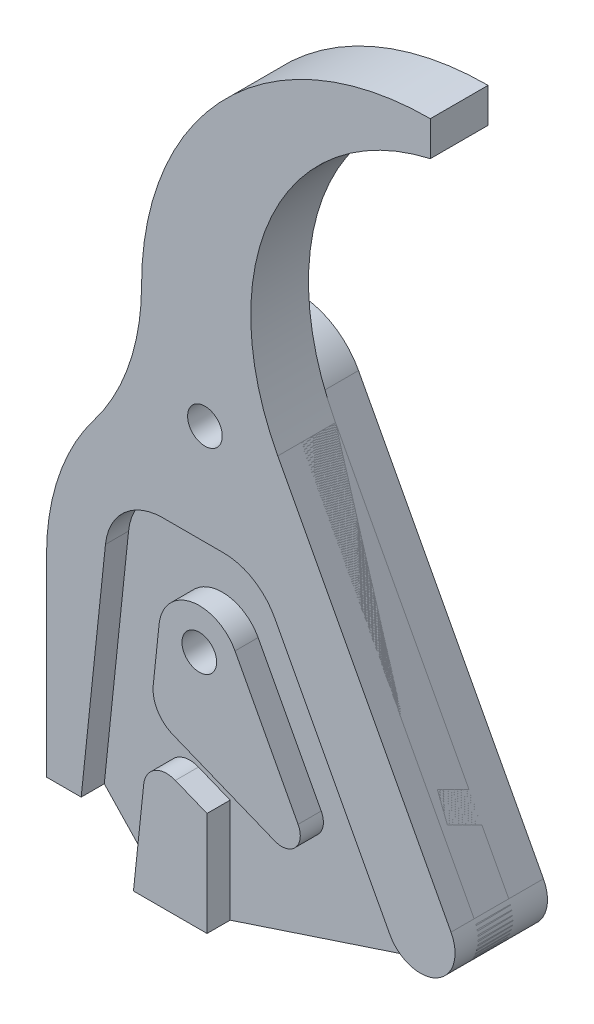
SolidWorks part; units mm, degrees
ref_plane "Alzado" through (0, 0, 0) normal (0, 0, 1) x (1, 0, 0)
ref_plane "Planta" through (0, 0, 0) normal (0, 1, 0) x (1, 0, 0)
ref_plane "Vista lateral" through (0, 0, 0) normal (1, 0, 0) x (0, 0, -1)
sketch "Croquis1" plane through (0, 0, 0) normal (0, 0, 1) x (1, 0, 0)
  line L0 (0, 0) -> (3.2081, 30.5226)
  line L1 (8.1807, 35) -> (13.4351, 35)
  line L2 (17.8498, 32.3474) -> (74.7762, -74.7155)
  line L3 (-45.5316, -5.3258) -> (-45.5316, 25.382)
  line L4 (0, 0) -> (0, 124.083) construction
  line L5 (14.4224, 28.1432) -> (19.8837, 17.8719)
  line L6 (7.8513, 26.8658) -> (7.3413, 22.014)
  line L7 (17.8498, 32.3474) -> (5.7848, 55.0384) construction
  line L8 (5.7848, 55.0384) -> (3.2081, 30.5226) construction
  line L9 (17.8538, 15.6175) -> (9.0466, 19.1759)
  line L10 (25.2121, 15.5) -> (11.8352, 15.5) construction
  line L11 (12.9137, 30) -> (5.536, 30) construction
  line L12 (6.4174, 22.7498) -> (9.4633, 17.0212) construction
  line L13 (5.0275, 0) -> (6.521, 14.2091)
  line L14 (9.2592, 15.8544) -> (17.7727, 12.4147)
  line L15 (6.3558, 16) -> (10.5824, 16) construction
  arc A0 (14.4224, 28.1432) -> (7.8513, 26.8658) centre (11.3321, 26.5) ccw
  arc A1 (17.8498, 32.3474) -> (13.4351, 35) centre (13.4351, 30) ccw
  arc A2 (8.1807, 35) -> (3.2081, 30.5226) centre (8.1807, 30) ccw
  arc A3 (7.3413, 22.014) -> (9.0466, 19.1759) centre (10.0771, 21.7264) ccw
  arc A4 (19.8837, 17.8719) -> (17.8538, 15.6175) centre (18.4585, 17.1142) cw
  arc A5 (6.521, 14.2091) -> (9.2592, 15.8544) centre (8.51, 14) cw
  dimension "D2" = 3.5
  dimension "D3" = 5
  dimension "D6" = 5
  dimension "D9" = 35
  dimension "D8" = 5
  dimension "D16" = 2
  dimension "D1" = 34
  dimension "D4" = 6
  dimension "D5" = 5
  dimension "D7" = 8.5
  dimension "D10" = 106
  dimension "D11" = 14.5
  dimension "D12" = 9.6
  dimension "D13" = 3
  dimension "D14" = 16
  dimension "D15" = 5
sketch "Croquis4" plane through (0, 0, 0) normal (0, 0, 1) x (1, 0, 0)
  line L0 (8.1807, 35) -> (13.4351, 35) construction
  line L1 (31.3321, 76.5) -> (69.3272, 76.5) construction
  line L2 (31.3321, 76.5) -> (31.3321, 73.5)
  line L3 (17.8538, 15.6175) -> (9.0466, 19.1759) construction
  line L5 (8.1807, 35) -> (13.4351, 35)
  line L6 (7.8513, 26.8658) -> (7.3413, 22.014)
  line L7 (7.8513, 26.8658) -> (7.3413, 22.014) construction
  line L8 (3.2081, 30.5226) -> (1.106, 10.5226)
  line L9 (0, 0) -> (3.2081, 30.5226) construction
  line L10 (17.8498, 32.3474) -> (27.8225, 13.5916)
  line L11 (17.8498, 32.3474) -> (74.7762, -74.7155) construction
  line L12 (6.521, 14.2091) -> (5.6316, 5.747)
  line L13 (14.4224, 28.1432) -> (19.8837, 17.8719) construction
  line L14 (17.8538, 15.6175) -> (9.0466, 19.1759)
  line L15 (1.106, 10.5226) -> (-1.894, 10.5226)
  line L16 (-1.894, 10.5226) -> (-1.894, 27.2014)
  line L17 (14.4224, 28.1432) -> (19.8837, 17.8719)
  line L18 (33.1201, 16.4084) -> (18.124, 44.6121)
  line L19 (5.0275, 0) -> (6.521, 14.2091) construction
  line L20 (9.2592, 15.8544) -> (12, 14.747)
  line L21 (9.2592, 15.8544) -> (17.7727, 12.4147) construction
  line L22 (12, 14.747) -> (12, 5.747)
  line L23 (12, 5.747) -> (5.6316, 5.747)
  line L25 (0, 0) -> (0, 124.083) construction
  line L26 (6.3321, 51.5) -> (-1.894, 27.2014) construction
  line L27 (17.8498, 32.3474) -> (5.7848, 55.0384) construction
  arc A0 (17.8498, 32.3474) -> (13.4351, 35) centre (13.4351, 30) ccw construction
  arc A1 (8.1807, 35) -> (3.2081, 30.5226) centre (8.1807, 30) ccw construction
  arc A2 (14.4224, 28.1432) -> (7.8513, 26.8658) centre (11.3321, 26.5) ccw construction
  arc A3 (17.8498, 32.3474) -> (13.4351, 35) centre (13.4351, 30) ccw
  arc A4 (8.1807, 35) -> (3.2081, 30.5226) centre (8.1807, 30) ccw
  arc A5 (14.4224, 28.1432) -> (7.8513, 26.8658) centre (11.3321, 26.5) ccw
  circle A6 centre (11.3321, 26.5) radius 1.5
  arc A7 (27.8225, 13.5916) -> (33.1201, 16.4084) centre (30.4713, 15) ccw
  arc A8 (7.3413, 22.014) -> (9.0466, 19.1759) centre (10.0771, 21.7264) ccw construction
  arc A9 (31.3321, 76.5) -> (6.3321, 51.5) centre (31.3321, 51.5) ccw
  arc A10 (31.3321, 73.5) -> (18.124, 44.6121) centre (35.7829, 54.0015) ccw
  arc A11 (17.8538, 15.6175) -> (19.8837, 17.8719) centre (18.4585, 17.1142) ccw construction
  arc A12 (7.3413, 22.014) -> (9.0466, 19.1759) centre (10.0771, 21.7264) ccw
  arc A13 (17.8538, 15.6175) -> (19.8837, 17.8719) centre (18.4585, 17.1142) ccw
  arc A14 (6.521, 14.2091) -> (9.2592, 15.8544) centre (8.51, 14) cw
  arc A15 (6.3321, 51.5) -> (2.219, 39.3507) centre (-13.6679, 51.5) cw
  arc A16 (2.219, 39.3507) -> (-1.894, 27.2014) centre (18.106, 27.2014) ccw
  circle A17 centre (11.8173, 43.6929) radius 1.5
  dimension "D1" = 3
  dimension "D9" = 3
  dimension "D6" = 20
  dimension "D12" = 20
  dimension "D13" = 20
  dimension "D14" = 25
  dimension "D15" = 3
  dimension "D2" = 20
  dimension "D3" = 3
  dimension "D4" = 20
  dimension "D5" = 3
  dimension "D7" = 50
  dimension "D8" = 20
  dimension "D10" = 12
  dimension "D11" = 9
extrude "Saliente-Extruir1" add sketch "Croquis4" along normal blind 5
sketch "Croquis5" plane through (0, 0, 0) normal (0, 0, 1) x (1, 0, 0)
  line L3 (-1.894, 10.5226) -> (-1.894, 27.2014) construction
  line L4 (1.106, 10.5226) -> (-1.894, 10.5226) construction
  line L8 (33.1201, 16.4084) -> (18.124, 44.6121) construction
  line L13 (12, 5.747) -> (5.6316, 5.747) construction
  line L14 (12, 5.747) -> (31.4112, 12.151)
  line L15 (1.106, 10.5226) -> (5.6316, 5.747)
  line L16 (3.6956, 41.5749) -> (6.6082, 46.6704)
  line L17 (-1.894, 10.5226) -> (-1.894, 27.2014)
  line L18 (1.106, 10.5226) -> (-1.894, 10.5226)
  line L22 (33.1201, 16.4084) -> (17.115, 46.5097)
  line L27 (12, 5.747) -> (5.6316, 5.747)
  arc A0 (2.219, 39.3507) -> (3.6956, 41.5749) centre (-13.6679, 51.5) ccw
  circle A4 centre (11.8173, 43.6929) radius 1.5 construction
  arc A6 (2.219, 39.3507) -> (-1.894, 27.2014) centre (18.106, 27.2014) ccw construction
  arc A13 (33.1201, 16.4084) -> (31.4112, 12.151) centre (30.4713, 15) cw
  circle A14 centre (11.3321, 26.5) radius 1.5 construction
  circle A15 centre (11.3321, 26.5) radius 1.5
  arc A16 (17.115, 46.5097) -> (6.6082, 46.6704) centre (11.8173, 43.6929) ccw
  circle A17 centre (11.8173, 43.6929) radius 1.5
  arc A19 (2.219, 39.3507) -> (-1.894, 27.2014) centre (18.106, 27.2014) ccw
  arc A20 (2.219, 39.3507) -> (6.3321, 51.5) centre (-13.6679, 51.5) ccw construction
extrude "Saliente-Extruir2" add sketch "Croquis5" against normal blind 3
sketch "Croquis6" plane through (0, 0, 0) normal (0, 0, 1) x (1, 0, 0)
  line L0 (33.1201, 16.4084) -> (17.115, 46.5097) construction
  line L1 (3.6956, 41.5749) -> (6.6082, 46.6704) construction
  line L2 (-1.894, 10.5226) -> (-1.894, 27.2014) construction
  line L3 (33.1201, 16.4084) -> (17.115, 46.5097)
  line L4 (3.6956, 41.5749) -> (6.6082, 46.6704)
  line L5 (-1.894, 10.5226) -> (-1.894, 27.2014)
  line L6 (12, 5.747) -> (31.4112, 12.151) construction
  line L7 (12, 5.747) -> (5.6316, 5.747) construction
  line L8 (1.106, 10.5226) -> (5.6316, 5.747) construction
  line L9 (1.106, 10.5226) -> (-1.894, 10.5226) construction
  line L10 (12, 5.747) -> (31.4112, 12.151)
  line L11 (12, 5.747) -> (5.6316, 5.747)
  line L12 (1.106, 10.5226) -> (5.6316, 5.747)
  line L13 (1.106, 10.5226) -> (-1.894, 10.5226)
  arc A0 (17.115, 46.5097) -> (6.6082, 46.6704) centre (11.8173, 43.6929) ccw construction
  arc A1 (2.219, 39.3507) -> (3.6956, 41.5749) centre (-13.6679, 51.5) ccw construction
  arc A2 (2.219, 39.3507) -> (-1.894, 27.2014) centre (18.106, 27.2014) ccw construction
  arc A3 (17.115, 46.5097) -> (6.6082, 46.6704) centre (11.8173, 43.6929) ccw
  arc A4 (2.219, 39.3507) -> (3.6956, 41.5749) centre (-13.6679, 51.5) ccw
  arc A5 (2.219, 39.3507) -> (-1.894, 27.2014) centre (18.106, 27.2014) ccw
  arc A6 (31.4112, 12.151) -> (33.1201, 16.4084) centre (30.4713, 15) ccw construction
  arc A7 (31.4112, 12.151) -> (33.1201, 16.4084) centre (30.4713, 15) ccw
  circle A8 centre (11.8173, 43.6929) radius 1.5 construction
  circle A9 centre (11.3321, 26.5) radius 1.5 construction
  circle A10 centre (11.8173, 43.6929) radius 1.5
  circle A11 centre (11.3321, 26.5) radius 1.5
extrude "Saliente-Extruir3" add sketch "Croquis6" along normal blind 3 separate body
